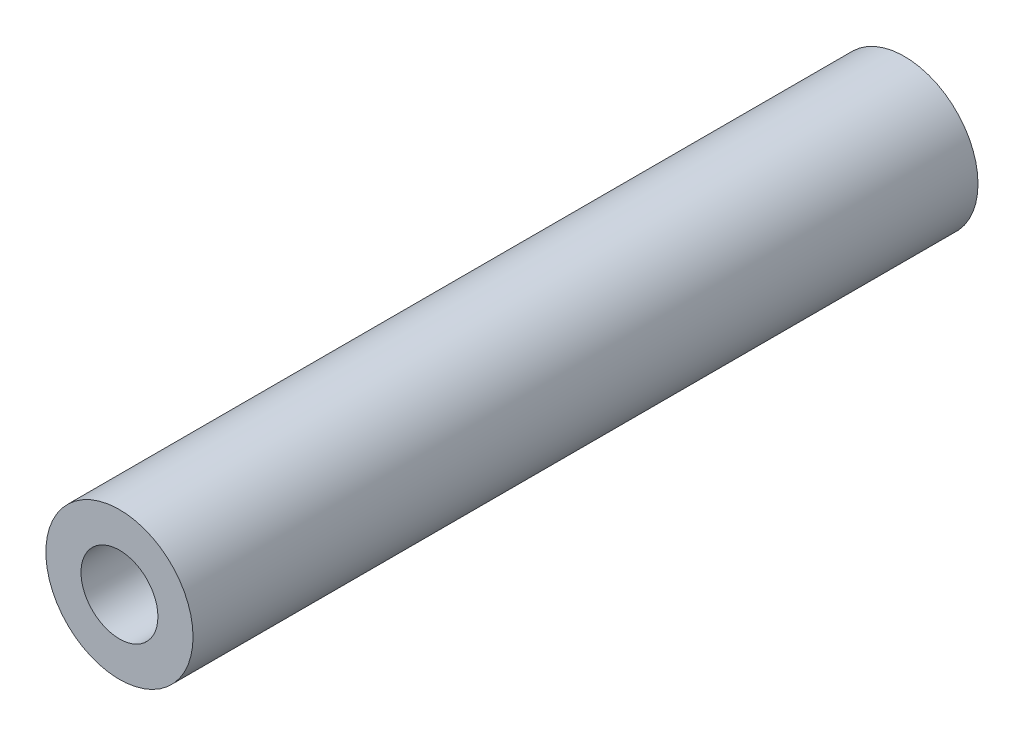
SolidWorks part; units mm, degrees
ref_plane "Front Plane" through (0, 0, 0) normal (0, 0, 1) x (1, 0, 0)
ref_plane "Top Plane" through (0, 0, 0) normal (0, 1, 0) x (1, 0, 0)
ref_plane "Right Plane" through (0, 0, 0) normal (1, 0, 0) x (0, 0, -1)
sketch "Sketch1" plane through (0, 0, 0) normal (0, 0, 1) x (1, 0, 0)
  circle A0 centre (0, 0) radius 4.7625
  circle A1 centre (0, 0) radius 2.4892
  dimension "D1" = 4.9784
  dimension "D2" = 9.525
extrude "Boss-Extrude1" add sketch "Sketch1" along normal blind 50.8
